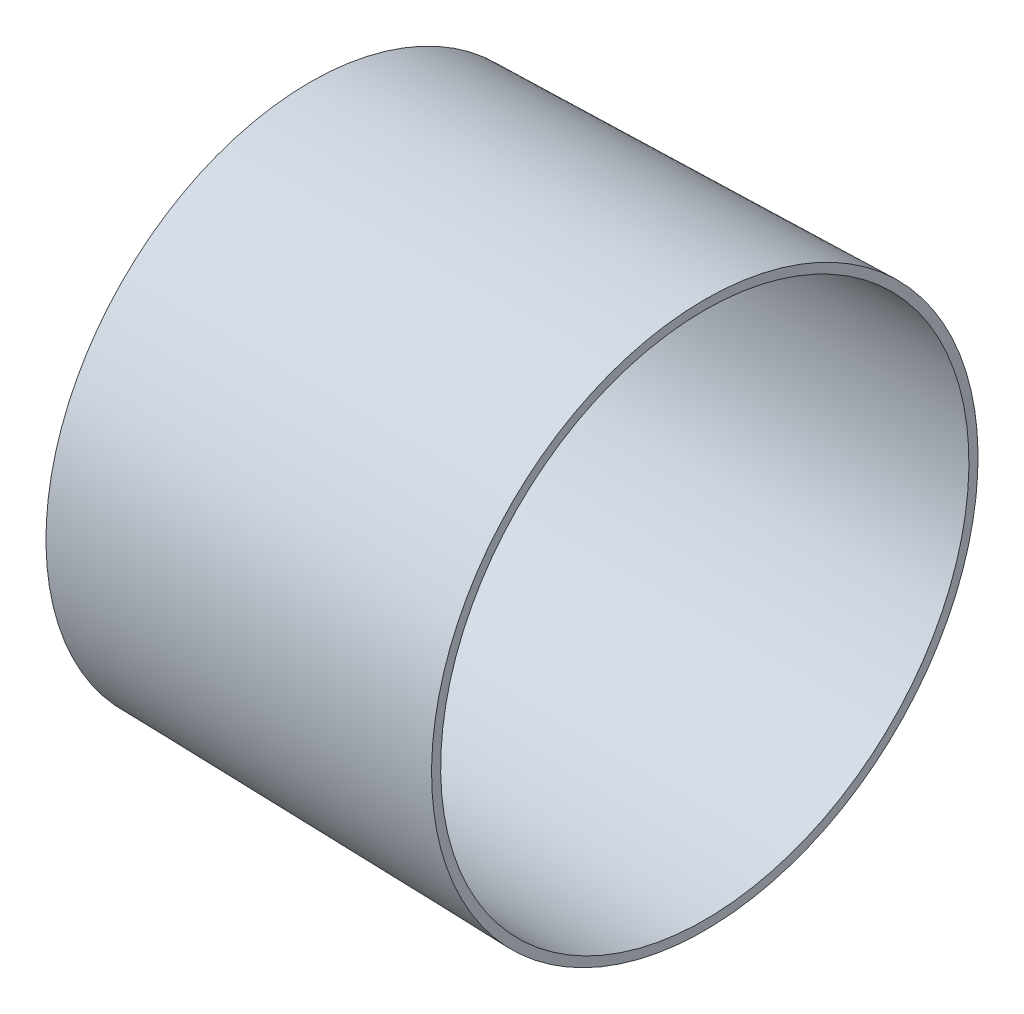
SolidWorks part; units mm, degrees
ref_plane "Front Plane" through (0, 0, 0) normal (0, 0, 1) x (1, 0, 0)
ref_plane "Top Plane" through (0, 0, 0) normal (0, 1, 0) x (1, 0, 0)
ref_plane "Right Plane" through (0, 0, 0) normal (1, 0, 0) x (0, 0, -1)
sketch "Sketch1" plane through (0, 0, 0) normal (0, 0, 1) x (1, 0, 0)
  line L0 (0, 0) -> (5000, 0) construction
  line L1 (3700, 420) -> (3700, 435)
  line L2 (3700, 435) -> (4350, 450)
  line L3 (4350, 450) -> (4350, 435)
  line L4 (4350, 435) -> (3700, 420)
revolve "Revolve1" add sketch "Sketch1" angle 360 about L0
